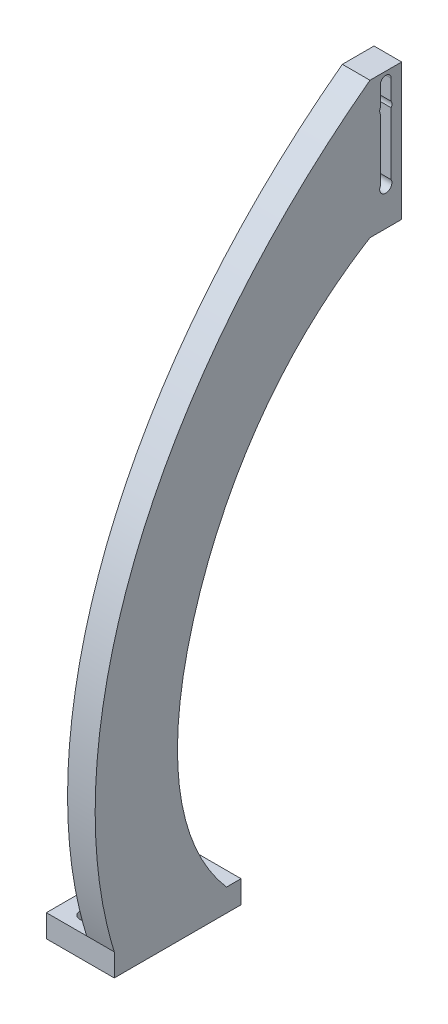
SolidWorks part; units mm, degrees
ref_plane "前视基准面" through (0, 0, 0) normal (0, 0, 1) x (1, 0, 0)
ref_plane "上视基准面" through (0, 0, 0) normal (0, 1, 0) x (1, 0, 0)
ref_plane "右视基准面" through (0, 0, 0) normal (1, 0, 0) x (0, 0, -1)
other "Configuration Table"
sketch "草图1" plane through (0, 0, 0) normal (0, 1, 0) x (1, 0, 0)
  line L0 (0, 0) -> (0, 10.0707) construction
  line L1 (-10, 14) -> (10, 14)
  line L2 (-10, 14) -> (-10, -14)
  line L3 (-10, -14) -> (10, -14)
  line L4 (10, 14) -> (10, -14)
  line L5 (-10, 14) -> (10, -14) construction
  line L6 (-10, -14) -> (10, 14) construction
  line L7 (0, 0) -> (4.3744, 0) construction
  circle A0 centre (-5, 10) radius 1.6
  circle A3 centre (-5, -10) radius 1.6
  point P0 (0, 0)
  dimension "D3" = 3.2
  dimension "D1" = 20
  dimension "D2" = 28
  dimension "D4" = 5
  dimension "D5" = 10
extrude "凸台-拉伸1" add sketch "草图1" along normal blind 5
sketch "草图2" plane through (0, 0, 0) normal (1, 0, 0) x (0, 0, -1)
  line L0 (42.4824, -6.5) -> (42.4824, 293.5) construction
  line L1 (-14, 5) -> (14, 5) construction
  line L2 (42.4824, 143.5) -> (42.4824, 113.3748)
  line L3 (-14, 5) -> (10.7943, 5)
  spline S0 degree 3 poles (-14, 5) (-21.091, 28.0724) (-16.0596, 83.5996) (19.3189, 126.3074) (42.4824, 143.5) knots 0 0 0 0 0.452387 1 1 1 1
  spline S1 degree 3 poles (10.7943, 5) (-3.6255, 21.7002) (-0.0389, 68.5305) (24.7866, 102.5635) (42.4824, 113.3748) knots 0 0 0 0 0.510479 1 1 1 1
extrude "凸台-拉伸2" add sketch "草图2" along normal blind 5 and the other way up to surface (1.1 mm away)
sketch "草图3" plane through (0, 0, -42.4824) normal (0, 0, -1) x (-1, 0, 0)
  line L4 (-5, 113.3748) -> (1.1, 113.3748)
  line L5 (1.1, 113.3748) -> (1.1, 143.5)
  line L6 (1.1, 143.5) -> (-5, 143.5)
  line L7 (-5, 143.5) -> (-5, 113.3748)
  line L8 (-5, 113.3748) -> (1.1, 113.3748)
  line L9 (1.1, 113.3748) -> (1.1, 143.5)
  line L10 (1.1, 143.5) -> (-5, 143.5)
  line L11 (-5, 143.5) -> (-5, 113.3748)
  dimension "D1" = 0
extrude "凸台-拉伸3" add sketch "草图3" along normal blind 7
sketch "草图4" plane through (5, 0, 0) normal (1, 0, 0) x (0, 0, -1)
  circle A0 centre (45.9824, 136.5) radius 1.35
  circle A1 centre (45.9824, 121.5) radius 1.35
  dimension "D1" = 2.7
extrude "切除-拉伸1" cut sketch "草图4" against normal blind 7
sketch "草图5" plane through (0, 5, 0) normal (0, 1, 0) x (1, 0, 0)
  line L0 (5, -18.2159) -> (5, 42.4824) construction
  line L1 (10, -14) -> (5, -14)
  line L2 (10, -14) -> (10, 14)
  line L3 (10, 14) -> (5, 14)
  line L4 (5, -14) -> (5, 14)
  line L5 (10, 14) -> (-10, 14) construction
extrude "切除-拉伸2" cut sketch "草图5" against normal blind 10
sketch "草图6" plane through (5, 0, 0) normal (1, 0, 0) x (0, 0, -1)
  line L0 (45.9824, 121.5) -> (45.9824, 141.5) construction
  line L1 (44.7824, 121.5) -> (44.7824, 141.5)
  line L2 (47.1824, 121.5) -> (47.1824, 141.5)
  arc A0 (44.7824, 121.5) -> (47.1824, 121.5) centre (45.9824, 121.5) ccw
  arc A1 (47.1824, 141.5) -> (44.7824, 141.5) centre (45.9824, 141.5) ccw
  point P3 (45.9824, 131.5)
  dimension "D1" = 1.2
  dimension "D2" = 20
extrude "切除-拉伸3" cut sketch "草图6" against normal blind 10
